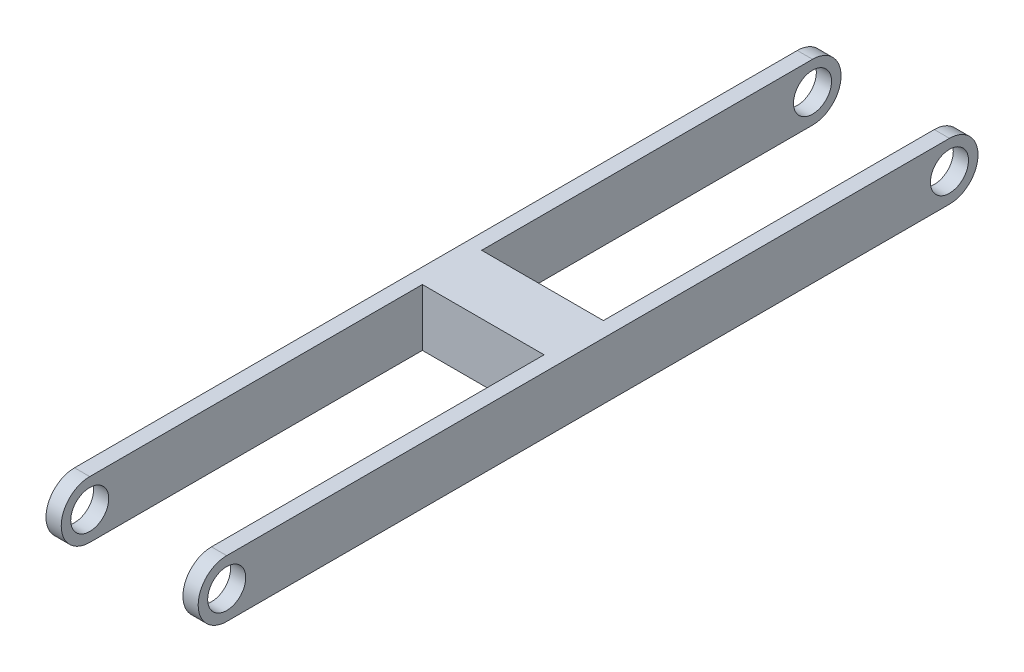
SolidWorks part; units mm, degrees
ref_plane "Front Plane" through (0, 0, 0) normal (0, 0, 1) x (1, 0, 0)
ref_plane "Top Plane" through (0, 0, 0) normal (0, 1, 0) x (1, 0, 0)
ref_plane "Right Plane" through (0, 0, 0) normal (1, 0, 0) x (0, 0, -1)
sketch "Sketch1" plane through (0, 0, 0) normal (1, 0, 0) x (0, 0, -1)
  line L0 (-47.5, 0) -> (47.5, 0) construction
  line L1 (47.5, 3.75) -> (-47.5, 3.75)
  line L3 (47.5, -3.75) -> (-47.5, -3.75)
  line L5 (47.5, 3.75) -> (-47.5, -3.75) construction
  line L6 (47.5, -3.75) -> (-47.5, 3.75) construction
  circle A0 centre (-47.5, 0) radius 2.5
  circle A1 centre (47.5, 0) radius 2.5
  arc A2 (47.5, 3.75) -> (47.5, -3.75) centre (47.5, 0) cw
  arc A3 (-47.5, -3.75) -> (-47.5, 3.75) centre (-47.5, 0) cw
  point P0 (0, 0)
  dimension "D2" = 5
  dimension "D3" = 5
  dimension "D1" = 95
  dimension "D4" = 7.5
extrude "Boss-Extrude1" add sketch "Sketch1" along normal blind 20
sketch "Sketch2" plane through (0, 3.75, 0) normal (0, 1, 0) x (1, 0, 0)
  line L0 (10, -51.25) -> (10, 51.25) construction
  line L2 (0, -51.25) -> (20, -51.25) construction
  line L3 (2, 51.25) -> (18, 51.25)
  line L4 (2, 51.25) -> (2, 4.0102)
  line L5 (2, -51.25) -> (18, -51.25)
  line L6 (18, 51.25) -> (18, 4.0102)
  line L7 (2, 51.25) -> (9.374, 4.0102) construction
  line L8 (2, -51.25) -> (9.4101, -3.7792) construction
  line L9 (2, -3.7792) -> (18, -3.7792)
  line L10 (2, 4.0102) -> (18, 4.0102)
  line L11 (18, -3.7792) -> (18, -51.25)
  line L12 (10.5899, -3.7792) -> (18, -51.25) construction
  line L13 (10.626, 4.0102) -> (18, 51.25) construction
  line L14 (0, 47.5) -> (0, -47.5) construction
  line L15 (2, -3.7792) -> (2, -51.25)
  line L16 (20, 47.5) -> (20, -47.5) construction
  point P5 (10, 0)
  dimension "D1" = 16
extrude "Cut-Extrude1" cut sketch "Sketch2" against normal through all both and the other way through all
